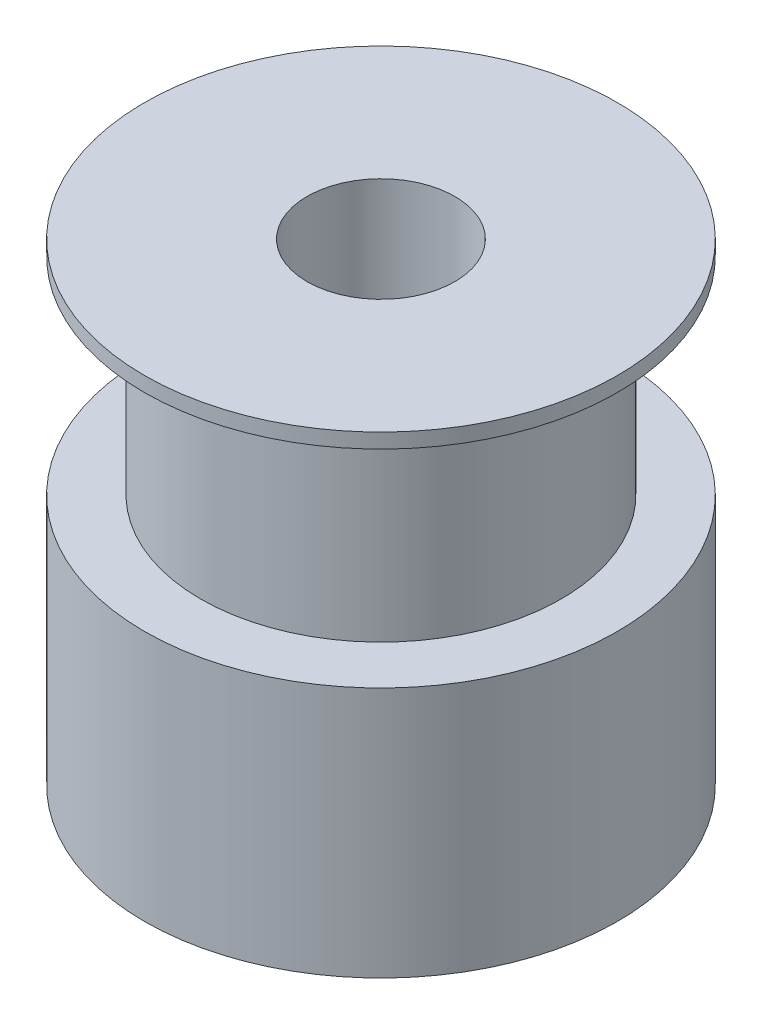
SolidWorks part; units mm, degrees
ref_plane "Спереди" through (0, 0, 0) normal (0, 0, 1) x (1, 0, 0)
ref_plane "Сверху" through (0, 0, 0) normal (0, 1, 0) x (1, 0, 0)
ref_plane "Справа" through (0, 0, 0) normal (1, 0, 0) x (0, 0, -1)
sketch "Sketch1" plane through (0, 0, 0) normal (0, 1, 0) x (1, 0, 0)
  circle A0 centre (0, 0) radius 8
  circle A1 centre (0, 0) radius 2.5
  dimension "D1" = 16
  dimension "D2" = 5
extrude "Boss-Extrude1" add sketch "Sketch1" along normal blind 16
ref_plane "Plane1" through (0, 15.5, 0) normal (0, 1, 0) x (1, 0, 0)
sketch "Sketch2" plane through (0, 15.5, 0) normal (0, 1, 0) x (1, 0, 0)
  circle A0 centre (0, 0) radius 6.1
  circle A1 centre (0, 0) radius 8.5197
  dimension "D1" = 12.2
extrude "Cut-Extrude1" cut sketch "Sketch2" against normal blind 7
